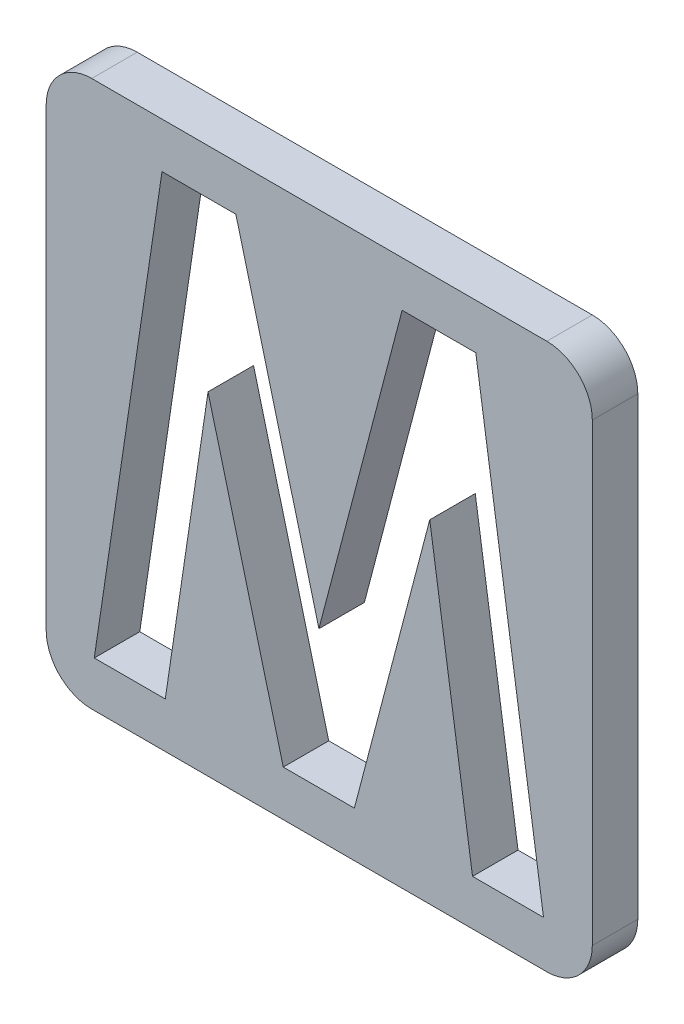
SolidWorks part; units mm, degrees
ref_plane "Front Plane" through (0, 0, 0) normal (0, 0, 1) x (1, 0, 0)
ref_plane "Top Plane" through (0, 0, 0) normal (0, 1, 0) x (1, 0, 0)
ref_plane "Right Plane" through (0, 0, 0) normal (1, 0, 0) x (0, 0, -1)
sketch "Sketch1" plane through (0, 0, 0) normal (0, 0, 1) x (1, 0, 0)
  line L1 (-50, 60) -> (50, 60)
  line L2 (-60, 50) -> (-60, -50)
  line L3 (-50, -60) -> (50, -60)
  line L4 (60, 50) -> (60, -50)
  line L5 (-60, 60) -> (60, -60) construction
  line L6 (-60, -60) -> (60, 60) construction
  arc A0 (-60, -50) -> (-50, -60) centre (-50, -50) ccw
  arc A1 (50, -60) -> (60, -50) centre (50, -50) ccw
  arc A2 (50, 60) -> (60, 50) centre (50, 50) cw
  arc A3 (-50, 60) -> (-60, 50) centre (-50, 50) ccw
  point P0 (0, 0)
  dimension "D3" = 10
  dimension "D1" = 120
  dimension "D2" = 120
extrude "Boss-Extrude1" add sketch "Sketch1" along normal blind 10 contours A3 L2 A0 L3 A1 L4 A2 L1
sketch "Sketch2" plane through (0, 0, 10) normal (0, 0, 1) x (1, 0, 0)
  line L0 (0, 0) -> (0, 40) construction
  line L1 (-50, 50) -> (50, 50) construction
  line L2 (-50, 50) -> (-50, -50) construction
  line L3 (-50, -50) -> (50, -50) construction
  line L4 (50, 50) -> (50, -50) construction
  line L5 (-50, 50) -> (50, -50) construction
  line L6 (-50, -50) -> (50, 50) construction
  line L7 (0, 40) -> (-40, 40) construction
  line L8 (-40, 40) -> (-40, 0) construction
  line L9 (-40, 0) -> (0, 0) construction
  line L11 (0, 20) -> (-20, 20) construction
  line L12 (-20, 40) -> (-20, 20) construction
  circle A0 centre (0, 40) radius 4 construction
  circle A1 centre (0, 20) radius 4 construction
  circle A2 centre (0, 0) radius 4 construction
  circle A3 centre (-20, 20) radius 4 construction
  circle A4 centre (-20, 40) radius 4 construction
  circle A5 centre (-40, 40) radius 4 construction
  circle A6 centre (0, 0) radius 4 construction
  circle A7 centre (20, 0) radius 4 construction
  circle A8 centre (40, 0) radius 4 construction
  circle A9 centre (40, 20) radius 4 construction
  circle A10 centre (40, 40) radius 4 construction
  circle A11 centre (20, 20) radius 4 construction
  circle A12 centre (0, 0) radius 4 construction
  circle A13 centre (0, -20) radius 4 construction
  circle A14 centre (0, -40) radius 4 construction
  circle A15 centre (20, -40) radius 4 construction
  circle A16 centre (40, -40) radius 4 construction
  circle A17 centre (20, -20) radius 4 construction
  circle A18 centre (0, 0) radius 4 construction
  circle A19 centre (-20, 0) radius 4 construction
  circle A20 centre (-40, 0) radius 4 construction
  circle A21 centre (-40, -20) radius 4 construction
  circle A22 centre (-40, -40) radius 4 construction
  circle A23 centre (-20, -20) radius 4 construction
  text T0 "M" font "Century Gothic" height 100
  point P0 (0, 0)
  point P55 (0, 0)
  dimension "D4" = 8
  dimension "D1" = 100
  dimension "D2" = 100
  dimension "D3" = 40
  dimension "D5" = 4
extrude "Cut-Extrude26" cut sketch "Sketch2" against normal blind 10
